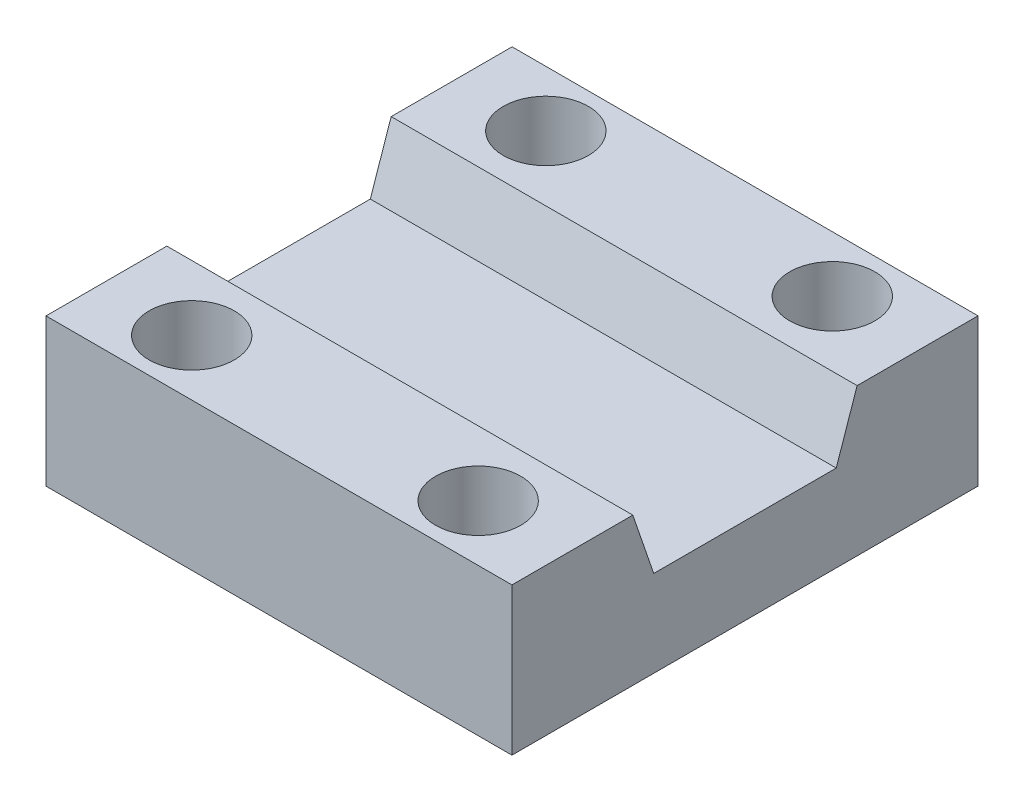
SolidWorks part; units mm, degrees
ref_plane "Front Plane" through (0, 0, 0) normal (0, 0, 1) x (1, 0, 0)
ref_plane "Top Plane" through (0, 0, 0) normal (0, 1, 0) x (1, 0, 0)
ref_plane "Right Plane" through (0, 0, 0) normal (1, 0, 0) x (0, 0, -1)
sketch "Sketch1" plane through (0, 0, 0) normal (0, 1, 0) x (1, 0, 0)
  line L6 (-19.145, 19.15) -> (19.145, 19.15)
  line L7 (-19.145, 19.15) -> (-19.145, -19.15)
  line L8 (-19.145, -19.15) -> (19.145, -19.15)
  line L9 (19.145, 19.15) -> (19.145, -19.15)
  line L10 (-19.145, 19.15) -> (19.145, -19.15) construction
  line L11 (-19.145, -19.15) -> (19.145, 19.15) construction
  point P11 (0, 0)
  dimension "D4" = 38.29
  dimension "D5" = 38.3
extrude "Boss-Extrude1" add sketch "Sketch1" along normal blind 12.12
sketch "Sketch2" plane through (19.145, 0, 0) normal (1, 0, 0) x (0, 0, -1)
  line L0 (-9.2164, 12.12) -> (-7.5, 7.11)
  line L1 (-19.15, 12.12) -> (19.15, 12.12) construction
  line L2 (-7.5, 7.11) -> (7.5, 7.11)
  line L3 (0, 7.11) -> (0, 0) construction
  line L4 (-9.2164, 12.12) -> (9.2164, 12.12)
  line L5 (9.2164, 12.12) -> (7.5, 7.11)
  line L6 (-19.15, 0) -> (19.15, 0) construction
  line L7 (-5.4456, 17.12) -> (6.1733, 17.12)
  line L8 (-7.6205, 12.12) -> (8.3482, 12.12)
  circle A0 centre (0.3638, 11.62) radius 8
  line M8 (19.15, 12.12) -> (-19.15, 12.12)
  dimension "D2" = 16
  dimension "D1" = 7.11
  dimension "D3" = 15
  dimension "D5" = 2.5
  dimension "D6" = 5
extrude "Cut-Extrude1" cut sketch "Sketch2" against normal through all contours L4 A0 L2 | A0 L0 L2 M8 | A0 L2 L5 M8
hole_wizard "M8x1.0 Tapped Hole2" positions "Sketch6" profile "Sketch7" tap size "M8x1.0" standard "ANSI Metric" end condition through all
sketch "Sketch6" plane through (0, 12.12, 0) normal (0, 1, 0) x (1, 0, 0)
  line L0 (0, 0) -> (-19.145, 0) construction
  line L4 (0, 0) -> (0, 19.15) construction
  line L5 (19.145, 19.15) -> (-19.145, 19.15) construction
  line L7 (-19.145, -7.5) -> (-19.145, 7.5) construction
  circle A1 centre (-11.77, 14.55) radius 4.125
  circle A2 centre (11.77, 14.55) radius 4.125
  circle A3 centre (11.77, -14.55) radius 4.125
  circle A4 centre (-11.77, -14.55) radius 4.125
  point P0 (-11.77, 14.55)
  point P18 (11.77, 14.55)
  point P25 (-11.77, -14.55)
  point P26 (11.77, -14.55)
  dimension "D1" = 8.25
  dimension "D2" = 15.29
  dimension "D3" = 20.85
sketch "Sketch7" plane through (-11.77, 12.12, -14.55) normal (1, 0, 0) x (0, 0, 1)
  line L0 (0, 0) -> (0, 12.12)
  line L1 (0, 12.12) -> (3.5, 12.12)
  line L2 (3.5, 12.12) -> (3.5, 0)
  line L5 (3.5, 0) -> (0, 0)
  line L11 (0, -6.35) -> (0, 107.95) construction
  dimension "Thru Tap Drill Dia." = 7
  dimension "Thru Tap Drill Depth" = 12.12
cosmetic thread "Hole Thread5" parameters "D2"=8
cosmetic thread "Hole Thread9" parameters "D2"=8
cosmetic thread "Hole Thread10" parameters "D2"=8
cosmetic thread "Hole Thread11" parameters "D2"=8
mirror "Mirror1" about plane through (0, 0, 0) normal (0, 0, 1) of "M8x1.0 Tapped Hole2" second plane through (0, 0, 0) second plane normal (1, 0, 0)
cosmetic thread "Hole Thread6" parameters "D2"=8
cosmetic thread "Hole Thread7" parameters "D2"=8
cosmetic thread "Hole Thread8" parameters "D2"=8
